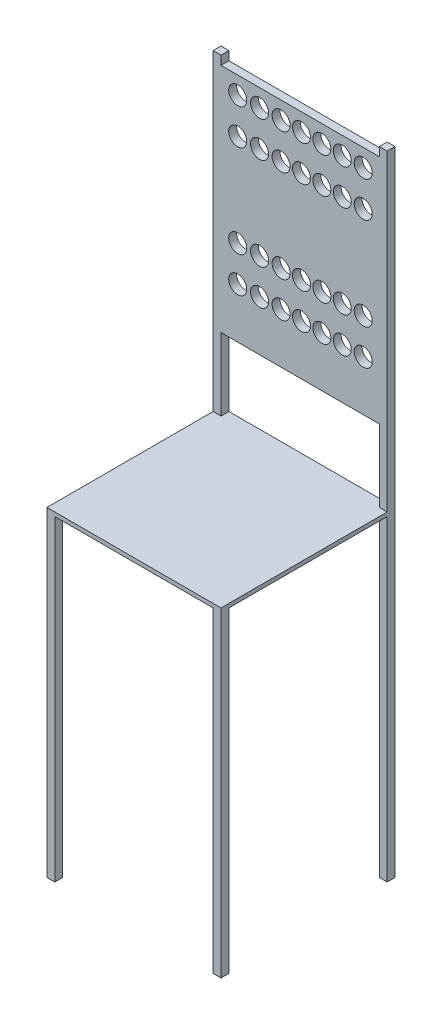
SolidWorks part; units mm, degrees
ref_plane "Front Plane" through (0, 0, 0) normal (0, 0, 1) x (1, 0, 0)
ref_plane "Top Plane" through (0, 0, 0) normal (0, 1, 0) x (1, 0, 0)
ref_plane "Right Plane" through (0, 0, 0) normal (1, 0, 0) x (0, 0, -1)
sketch "Sketch1" plane through (0, 0, 0) normal (0, 1, 0) x (1, 0, 0)
  line L0 (0, 107.724) -> (0, -97.0714) construction
  line L1 (-110, 110) -> (-100, 110)
  line L2 (-110, 110) -> (-110, 100)
  line L3 (-110, 100) -> (-100, 100)
  line L4 (-100, 110) -> (-100, 100)
  line L5 (-130.0613, 0) -> (191.5753, 0) construction
  line L6 (100, 110) -> (100, 100)
  line L7 (110, 100) -> (100, 100)
  line L8 (110, 110) -> (110, 100)
  line L9 (110, 110) -> (100, 110)
  line L10 (110, -110) -> (100, -110)
  line L11 (110, -110) -> (110, -100)
  line L12 (110, -100) -> (100, -100)
  line L13 (100, -110) -> (100, -100)
  line L14 (-100, -110) -> (-100, -100)
  line L15 (-110, -100) -> (-100, -100)
  line L16 (-110, -110) -> (-110, -100)
  line L17 (-110, -110) -> (-100, -110)
  dimension "D1" = 10
  dimension "D2" = 10
  dimension "D3" = 100
  dimension "D4" = 100
extrude "Boss-Extrude1" add sketch "Sketch1" along normal blind 400
sketch "Sketch2" plane through (0, 400, 0) normal (0, 1, 0) x (1, 0, 0)
  line L0 (110, 110) -> (100, 110) construction
  line L1 (100, 110) -> (100, 100) construction
  line L2 (100, 100) -> (110, 100) construction
  line L3 (110, 100) -> (110, 110) construction
  line L4 (-110, 110) -> (-110, 100) construction
  line L5 (-110, 100) -> (-100, 100) construction
  line L6 (-100, 100) -> (-100, 110) construction
  line L7 (-100, 110) -> (-110, 110) construction
  line L8 (110, 110) -> (100, 110)
  line L9 (100, 110) -> (100, 100)
  line L10 (100, 100) -> (110, 100)
  line L11 (110, 100) -> (110, 110)
  line L12 (-110, 110) -> (-110, 100)
  line L13 (-110, 100) -> (-100, 100)
  line L14 (-100, 100) -> (-100, 110)
  line L15 (-100, 110) -> (-110, 110)
extrude "Boss-Extrude2" add sketch "Sketch2" along normal blind 400
sketch "Sketch3" plane through (0, 400, 0) normal (0, 1, 0) x (1, 0, 0)
  line L1 (-110, 110) -> (110, 110)
  line L2 (-110, 110) -> (-110, -110)
  line L3 (-110, -110) -> (110, -110)
  line L4 (110, 110) -> (110, -110)
extrude "Boss-Extrude3" add sketch "Sketch3" along normal blind 5
sketch "Sketch4" plane through (-100, 0, 0) normal (1, 0, 0) x (0, 0, -1)
  line L0 (100, 800) -> (100, 405) construction
  line L1 (100, 788.8452) -> (110, 788.8452)
  line L2 (100, 788.8452) -> (100, 496.4207)
  line L3 (100, 496.4207) -> (110, 496.4207)
  line L4 (110, 788.8452) -> (110, 496.4207)
  line L5 (110, 800) -> (110, 0) construction
extrude "Boss-Extrude4" add sketch "Sketch4" along normal blind 200
sketch "Sketch5" plane through (0, 0, -100) normal (0, 0, 1) x (1, 0, 0)
  line L0 (-145.6598, 744.1548) -> (152.3168, 744.1548) construction
  line L1 (-145.6598, 663.2184) -> (152.3168, 663.2184) construction
  circle A0 centre (-78.8782, 766.6573) radius 11.3909
  circle A1 centre (-51.2945, 766.6573) radius 11.3909
  circle A2 centre (-24.0737, 766.6573) radius 11.3909
  circle A3 centre (1.6953, 766.6573) radius 11.3909
  circle A4 centre (27.4643, 766.6573) radius 11.3909
  circle A5 centre (53.2333, 766.6573) radius 11.3909
  circle A6 centre (79.7281, 766.6573) radius 11.3909
  circle A8 centre (79.7281, 721.6523) radius 11.3909
  circle A9 centre (53.2333, 721.6523) radius 11.3909
  circle A10 centre (27.4643, 721.6523) radius 11.3909
  circle A11 centre (1.6953, 721.6523) radius 11.3909
  circle A12 centre (-24.0737, 721.6523) radius 11.3909
  circle A13 centre (-51.2945, 721.6523) radius 11.3909
  circle A14 centre (-78.8782, 721.6523) radius 11.3909
  circle A15 centre (-78.8782, 604.7845) radius 11.3909
  circle A16 centre (-51.2945, 604.7845) radius 11.3909
  circle A17 centre (-24.0737, 604.7845) radius 11.3909
  circle A18 centre (1.6953, 604.7845) radius 11.3909
  circle A19 centre (27.4643, 604.7845) radius 11.3909
  circle A20 centre (53.2333, 604.7845) radius 11.3909
  circle A21 centre (79.7281, 604.7845) radius 11.3909
  circle A22 centre (79.7281, 559.7795) radius 11.3909
  circle A23 centre (53.2333, 559.7795) radius 11.3909
  circle A24 centre (27.4643, 559.7795) radius 11.3909
  circle A25 centre (1.6953, 559.7795) radius 11.3909
  circle A26 centre (-24.0737, 559.7795) radius 11.3909
  circle A27 centre (-51.2945, 559.7795) radius 11.3909
  circle A28 centre (-78.8782, 559.7795) radius 11.3909
extrude "Cut-Extrude1" cut sketch "Sketch5" against normal blind 200
